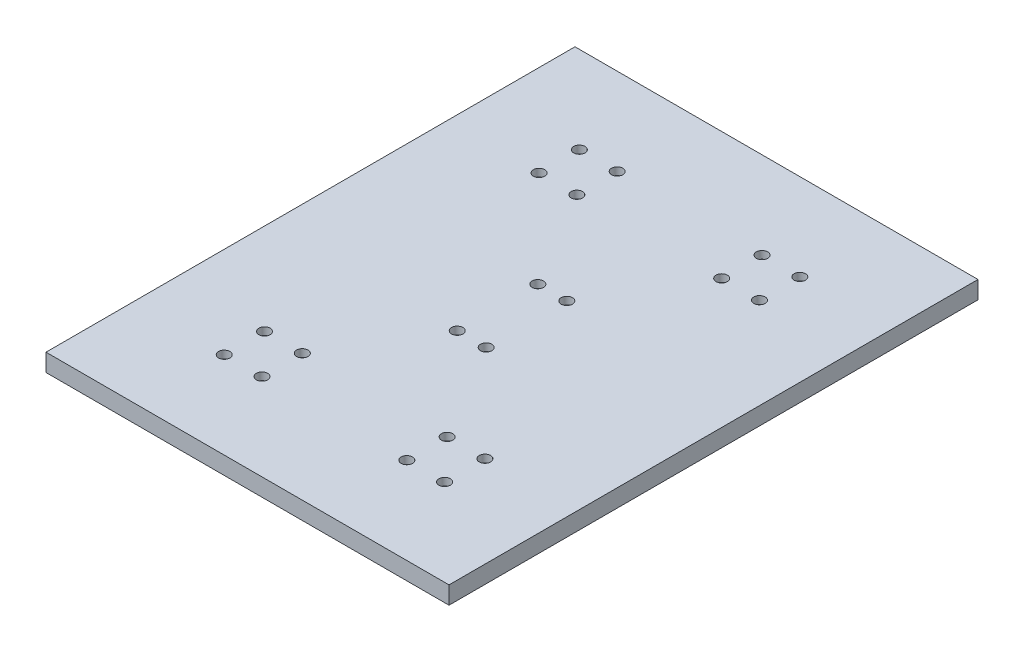
SolidWorks part; units mm, degrees
material "1.0037 (S235JR)"
ref_plane "Płaszczyzna przednia" through (0, 0, 0) normal (0, 0, 1) x (1, 0, 0)
ref_plane "Płaszczyzna górna" through (0, 0, 0) normal (0, 1, 0) x (1, 0, 0)
ref_plane "Płaszczyzna prawa" through (0, 0, 0) normal (1, 0, 0) x (0, 0, -1)
sketch "Szkic1" plane through (0, 0, 0) normal (0, 1, 0) x (1, 0, 0)
  line L1 (-160, -210) -> (160, -210)
  line L2 (-160, -210) -> (-160, 210)
  line L3 (-160, 210) -> (160, 210)
  line L4 (160, -210) -> (160, 210)
  line L5 (-160, -210) -> (160, 210) construction
  line L6 (-160, 210) -> (160, -210) construction
  point P0 (0, 0)
  dimension "D1" = 420
  dimension "D2" = 320
extrude "Dodanie-wyciągnięcie1" add sketch "Szkic1" along normal blind 14
sketch "Szkic2" plane through (0, 0, 0) normal (0, -1, 0) x (1, 0, 0)
  line L2 (-95, -147.5) -> (95, -147.5)
  line L3 (-95, -147.5) -> (-95, 147.5)
  line L4 (-95, 147.5) -> (95, 147.5)
  line L5 (95, -147.5) -> (95, 147.5)
  line L6 (-95, -147.5) -> (95, 147.5) construction
  line L7 (-95, 147.5) -> (95, -147.5) construction
  point P4 (0, 0)
  dimension "D1" = 190
  dimension "D2" = 295
hole_wizard "Pogłębienie walcowe pod M5 Wkręt do części metalowych z łbem sześciokątnym1" positions "Szkic7" profile "Szkic6" counterbore size "M5" standard "Ansi Metric" end condition through all
sketch "Szkic7" plane through (0, 14, 0) normal (0, 1, 0) x (1, 0, 0)
  point P0 (-87.5, -141)
  point P2 (-87.5, -109)
  point P4 (-57.5, -141)
  point P6 (-57.5, -109)
  point P8 (57.5, -141)
  point P10 (57.5, -109)
  point P12 (87.5, -109)
  point P14 (87.5, -141)
sketch "Szkic6" plane through (-87.5, 14, 141) normal (1, 0, 0) x (0, 0, 1)
  line L0 (0, 0) -> (0, 14)
  line L1 (0, 14) -> (2.75, 14)
  line L3 (2.75, 14) -> (2.75, 6)
  line L4 (2.75, 6) -> (4.5, 6)
  line L5 (4.5, 6) -> (4.5, 0)
  line L7 (4.5, 0) -> (0, 0)
  line L11 (0, -6.35) -> (0, 107.95) construction
  dimension "Średnica otworu na wylot" = 5.5
  dimension "Głębokość otworu na wylot" = 14
  dimension "Średnica pogłębienia walcowego" = 9
  dimension "Głębokość pogłębienia walcowego" = 6
mirror "Lustro3" about plane through (0, 0, 0) normal (0, 0, 1) of "Pogłębienie walcowe pod M5 Wkręt do części metalowych z łbem sześciokątnym1"
sketch "Szkic10" plane through (-160, 0, 0) normal (-1, 0, 0) x (0, 0, 1)
  line L1 (-35, 0) -> (35, 0)
  line L2 (-35, 0) -> (-35, 4)
  line L3 (-35, 4) -> (35, 4)
  line L4 (35, 0) -> (35, 4)
  dimension "D1" = 70
  dimension "D2" = 4
extrude "Wytnij-wyciągnięcie1" cut sketch "Szkic10" against normal blind 50
fillet "Zaokrąglenie1" radius 10 2 edges at (-110, 2, -35) (-110, 2, 35)
sketch "草图1" plane through (0, 14, 0) normal (0, 1, 0) x (1, 0, 0)
  line L0 (160, 0) -> (-245.0175, 0) construction
  line L1 (160, -210) -> (160, 210) construction
  line L2 (0, 210) -> (0, -345.7386) construction
  line L3 (160, 210) -> (-160, 210) construction
  circle A0 centre (11.5, 32) radius 4.5
  circle A1 centre (-11.5, 32) radius 4.5
  circle A2 centre (-11.5, -32) radius 4.5
  circle A3 centre (11.5, -32) radius 4.5
  dimension "D1" = 64
  dimension "D2" = 23
extrude "切除-拉伸1" cut sketch "草图1" against normal blind 6
sketch "草图2" plane through (0, 14, 0) normal (0, 1, 0) x (1, 0, 0)
  line L0 (160, 0) -> (-231.194, 0) construction
  line L1 (160, -210) -> (160, 210) construction
  line L2 (0, 210) -> (0, -258.8119) construction
  line L3 (160, 210) -> (-160, 210) construction
  circle A0 centre (11.5, 32) radius 2.75
  circle A1 centre (-11.5, 32) radius 2.75
  circle A2 centre (-11.5, -32) radius 2.75
  circle A3 centre (11.5, -32) radius 2.75
  dimension "D1" = 5.5
extrude "切除-拉伸2" cut sketch "草图2" against normal through all
